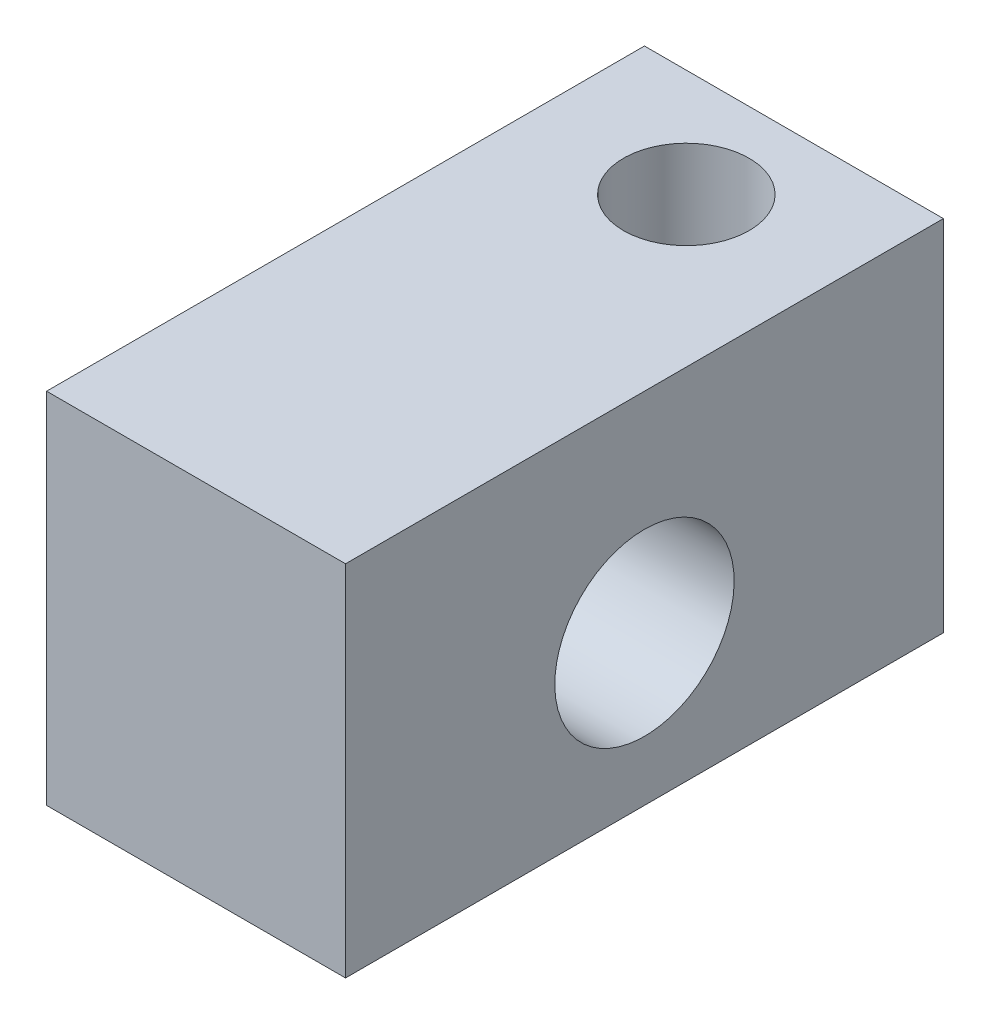
SolidWorks part; units mm, degrees
ref_plane "Front Plane" through (0, 0, 0) normal (0, 0, 1) x (1, 0, 0)
ref_plane "Top Plane" through (0, 0, 0) normal (0, 1, 0) x (1, 0, 0)
ref_plane "Right Plane" through (0, 0, 0) normal (1, 0, 0) x (0, 0, -1)
sketch "Sketch1" plane through (0, 0, 0) normal (0, 0, 1) x (1, 0, 0)
  line L1 (0, 0) -> (5, 0)
  line L2 (0, 0) -> (0, -6)
  line L3 (0, -6) -> (5, -6)
  line L4 (5, 0) -> (5, -6)
  dimension "D1" = 5
  dimension "D2" = 6
extrude "Boss-Extrude1" add sketch "Sketch1" along normal blind 10
sketch "Sketch2" plane through (5, 0, 0) normal (1, 0, 0) x (0, 0, -1)
  line L0 (-10, -6) -> (0, -6) construction
  line L1 (-5, -3.5) -> (-5, -6) construction
  circle A0 centre (-5, -3.5) radius 1.5
  dimension "D1" = 3
  dimension "D2" = 2.5
extrude "Cut-Extrude1" cut sketch "Sketch2" against normal up to next
sketch "Sketch3" plane through (0, 0, 0) normal (0, 1, 0) x (1, 0, 0)
  line L0 (5, -10) -> (5, 0) construction
  line L1 (5, 0) -> (0, 0) construction
  circle A0 centre (2.5, -1.8) radius 1.05
  dimension "D1" = 2.5
  dimension "D3" = 2.1
  dimension "D2" = 1.8
extrude "Cut-Extrude2" cut sketch "Sketch3" against normal blind 3.25
sketch "Sketch4" plane through (0, -6, 0) normal (0, -1, 0) x (1, 0, 0)
  line L0 (2.5, 9.25) -> (2.5, 10) construction
  line L1 (0, 10) -> (5, 10) construction
  circle A0 centre (2.5, 8.2) radius 1.05
  dimension "D2" = 2.1
  dimension "D1" = 0.75
extrude "Cut-Extrude3" cut sketch "Sketch4" against normal blind 1.75
